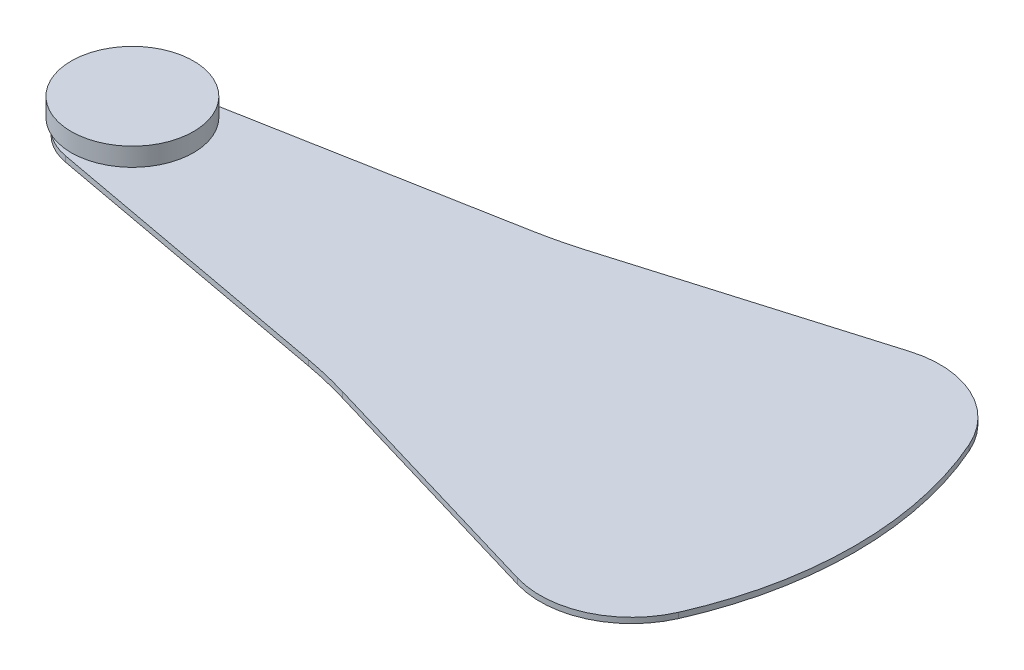
SolidWorks part; units mm, degrees
other "Camera1"
ref_plane "Front Plane" through (0, 0, 0) normal (0, 0, 1) x (1, 0, 0)
ref_plane "Top Plane" through (0, 0, 0) normal (0, 1, 0) x (1, 0, 0)
ref_plane "Right Plane" through (0, 0, 0) normal (1, 0, 0) x (0, 0, -1)
sketch "Sketch2" plane through (0, 113.481, 0) normal (0, -1, 0) x (1, 0, 0)
  line L0 (60.3729, 72.1945) -> (70.1254, 70.3945) construction
  line L1 (71.5841, 70.0445) -> (79.7331, 67.6273) construction
  line L2 (79.7331, 80.4618) -> (71.5841, 78.0445) construction
  line L3 (70.1254, 77.6946) -> (60.3729, 75.8945) construction
  line L4 (60.3729, 72.1945) -> (70.1254, 70.3945)
  line L5 (71.5841, 70.0445) -> (79.7331, 67.6273)
  line L6 (79.7331, 80.4618) -> (71.5841, 78.0445)
  line L7 (70.1254, 77.6946) -> (60.3729, 75.8945)
  arc A0 (60.3729, 75.8945) -> (60.3729, 72.1945) centre (60.7143, 74.0445) ccw construction
  arc A1 (71.5841, 70.0445) -> (70.1254, 70.3945) centre (67.5519, 56.4514) ccw construction
  arc A2 (79.7331, 67.6273) -> (83.3331, 69.2945) centre (80.5866, 70.5046) ccw construction
  arc A3 (83.3331, 69.2945) -> (84.3331, 74.0445) centre (72.5519, 74.0445) ccw construction
  arc A4 (84.3331, 74.0445) -> (83.3331, 78.7945) centre (72.5519, 74.0445) ccw construction
  arc A5 (83.3331, 78.7945) -> (79.7331, 80.4618) centre (80.5866, 77.5845) ccw construction
  arc A6 (70.1254, 77.6946) -> (71.5841, 78.0445) centre (67.5519, 91.6377) ccw construction
  arc A7 (60.3729, 75.8945) -> (60.3729, 72.1945) centre (60.7143, 74.0445) ccw
  arc A8 (71.5841, 70.0445) -> (70.1254, 70.3945) centre (67.5519, 56.4514) ccw
  arc A9 (79.7331, 67.6273) -> (83.3331, 69.2945) centre (80.5866, 70.5046) ccw
  arc A10 (83.3331, 69.2945) -> (84.3331, 74.0445) centre (72.5519, 74.0445) ccw
  arc A11 (84.3331, 74.0445) -> (83.3331, 78.7945) centre (72.5519, 74.0445) ccw
  arc A12 (83.3331, 78.7945) -> (79.7331, 80.4618) centre (80.5866, 77.5845) ccw
  arc A13 (70.1254, 77.6946) -> (71.5841, 78.0445) centre (67.5519, 91.6377) ccw
extrude "Boss-Extrude2" add sketch "Sketch2" against normal up to surface (0.18 mm away)
sketch "Sketch4" plane through (0, 113.481, 0) normal (0, -1, 0) x (1, 0, 0)
  circle A0 centre (60.7143, 74.0445) radius 1
  point P3 (61.7143, 74.0445)
  dimension "D1" = 2
extrude "Cut-Extrude1" cut sketch "Sketch4" against normal through all
ref_plane "Plane3" through (0, 113.991, 0) normal (0, 1, 0) x (1, 0, 0)
sketch "Sketch7" plane through (0, 113.991, 0) normal (0, 1, 0) x (1, 0, 0)
  circle A0 centre (60.7143, -74.0445) radius 2
  dimension "D1" = 4
extrude "Boss-Extrude3" add sketch "Sketch7" along normal blind 0.6 separate body
sketch "Sketch8" plane through (0, 113.661, 0) normal (0, 1, 0) x (1, 0, 0)
  circle A1 centre (60.7143, -74.0445) radius 1 construction
  circle A2 centre (60.7143, -74.0445) radius 1.4
  circle A3 centre (60.7143, -74.0445) radius 1.4
  circle A4 centre (60.7143, -74.0445) radius 1
  dimension "D1" = 0.4
extrude "Boss-Extrude4" add sketch "Sketch8" along normal up to next
